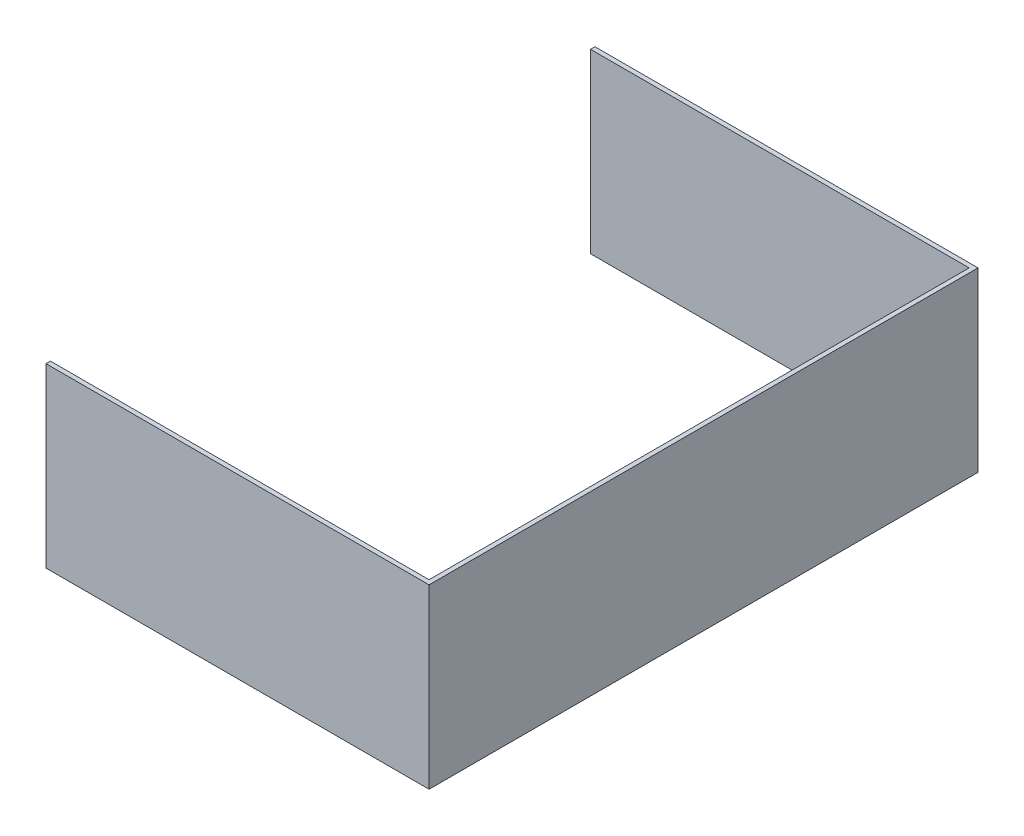
SolidWorks part; units mm, degrees
ref_plane "Alzado" through (0, 0, 0) normal (0, 0, 1) x (1, 0, 0)
ref_plane "Planta" through (0, 0, 0) normal (0, 1, 0) x (1, 0, 0)
ref_plane "Vista lateral" through (0, 0, 0) normal (1, 0, 0) x (0, 0, -1)
sketch "Croquis1" plane through (0, 0, 0) normal (0, 1, 0) x (1, 0, 0)
  line L0 (0, 152.5) -> (213.83, 152.5)
  line L1 (213.83, 152.5) -> (213.83, -152.5)
  line L2 (213.83, -152.5) -> (0, -152.5)
  line L3 (0, -152.5) -> (0, -155)
  line L4 (0, -155) -> (216.33, -155)
  line L5 (216.33, -155) -> (216.33, 155)
  line L6 (216.33, 155) -> (0, 155)
  line L7 (0, 155) -> (0, 152.5)
  point P3 (213.83, 0)
  point P10 (216.33, 0)
  dimension "D1" = 310
  dimension "D2" = 2.5
  dimension "D3" = 2.5
  dimension "D4" = 216.33
extrude "Saliente-Extruir1" add sketch "Croquis1" along normal blind 100
equation "\"D1@Croquis1\"=\"ancho_tot\""
equation "\"venesta\"= 4'grosor de la venesta"
equation "\"policarbonato\"= 4'grosor del policarbonato"
equation "\"carton_trupan\"= 3'grosor del carton trupan caso laser"
equation "\"ancho_tot\"= 310'ancho tot sin llantas"
equation "\"largo_tot\"= 400'largo tot sin camera"
equation "\"alto_estimado\"= 300'alto estimado sin lidar"
equation "\"altoparaqpaselabotella\"= 75'alto estimado para que encaje la botella"
equation "\"alturaruedaloca\"= 22"
equation "\"anchoruedaloca\"= 35"
equation "\"anchopiso1motorybaterias\"= 150"
equation "\"dist-pisorampa\"= 5"
equation "\"anchoultimopiso\"= 170"
equation "\"paredtrasera\"= 100"
equation "\"agarradorcanasta\"= 275'recolector"
equation "\"alturapiso1y2\"= 80"
equation "\"alturapiso2y3\"= 80"
equation "\"GROSOR_PARED_IMPRESION\"= 2.5"
equation "\"TOLERANCIA\"= 0.05"
equation "\"apertura\"= 70"
equation "\"D2@Croquis1\"=\"GROSOR_PARED_IMPRESION\""
equation "\"D3@Croquis1\"=\"GROSOR_PARED_IMPRESION\""
